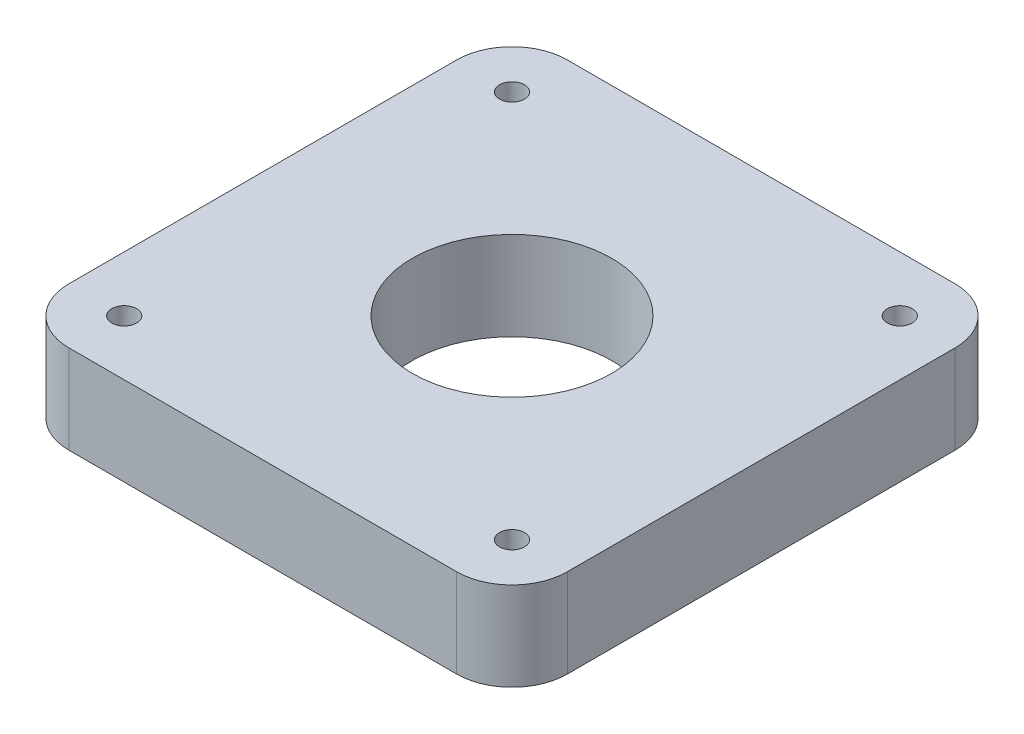
SolidWorks part; units mm, degrees
ref_plane "Front Plane" through (0, 0, 0) normal (0, 0, 1) x (1, 0, 0)
ref_plane "Top Plane" through (0, 0, 0) normal (0, 1, 0) x (1, 0, 0)
ref_plane "Right Plane" through (0, 0, 0) normal (1, 0, 0) x (0, 0, -1)
sketch "Sketch1" plane through (0, 0, 0) normal (0, 1, 0) x (1, 0, 0)
  line L1 (-17.5, 17.5) -> (17.5, 17.5)
  line L2 (-17.5, 17.5) -> (-17.5, -17.5)
  line L3 (-17.5, -17.5) -> (17.5, -17.5)
  line L4 (17.5, 17.5) -> (17.5, -17.5)
  line L5 (-17.5, 17.5) -> (17.5, -17.5) construction
  line L6 (-17.5, -17.5) -> (17.5, 17.5) construction
  line L7 (-22.5, -22.5) -> (22.5, -22.5)
  line L8 (-22.5, -22.5) -> (-22.5, 22.5)
  line L9 (-22.5, 22.5) -> (22.5, 22.5)
  line L10 (22.5, -22.5) -> (22.5, 22.5)
  line L11 (-22.5, -22.5) -> (22.5, 22.5) construction
  line L12 (-22.5, 22.5) -> (22.5, -22.5) construction
  circle A0 centre (0, 0) radius 9
  circle A1 centre (-17.5, 17.5) radius 1.125
  circle A2 centre (17.5, 17.5) radius 1.125
  circle A3 centre (17.5, -17.5) radius 1.125
  circle A4 centre (-17.5, -17.5) radius 1.125
  point P0 (0, 0)
  dimension "D1" = 35
  dimension "D2" = 18
  dimension "D3" = 5
extrude "Boss-Extrude1" add sketch "Sketch1" along normal blind 8 contours A4 L3 A3 L4 A2 L1 A1 L2 A0 | L7 L10 L9 L8 A4 L2 A1 L1 A2 L4 A3 L3
fillet "Fillet1" radius 5 4 edges at (-22.5, 4, -22.5) (22.5, 4, -22.5) (22.5, 4, 22.5) (-22.5, 4, 22.5)
